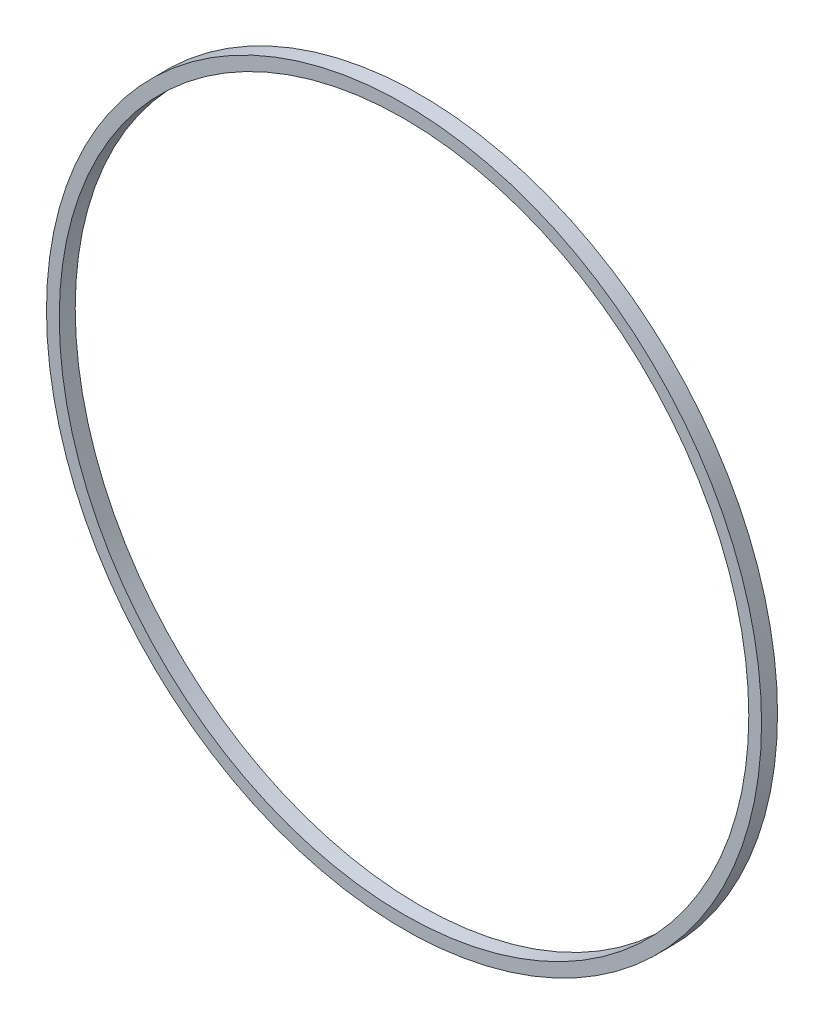
SolidWorks part; units mm, degrees
ref_plane "Front Plane" through (0, 0, 0) normal (0, 0, 1) x (1, 0, 0)
ref_plane "Top Plane" through (0, 0, 0) normal (0, 1, 0) x (1, 0, 0)
ref_plane "Right Plane" through (0, 0, 0) normal (1, 0, 0) x (0, 0, -1)
sketch "Sketch1" plane through (0, 0, 0) normal (0, 0, 1) x (1, 0, 0)
  circle A0 centre (0, 0) radius 56
extrude "Boss-Extrude1" add sketch "Sketch1" along normal blind 2.5
sketch "Sketch2" plane through (0, 0, 2.5) normal (0, 0, 1) x (1, 0, 0)
  circle A0 centre (0, 0) radius 54
extrude "Cut-Extrude1" cut sketch "Sketch2" against normal blind 2.5
